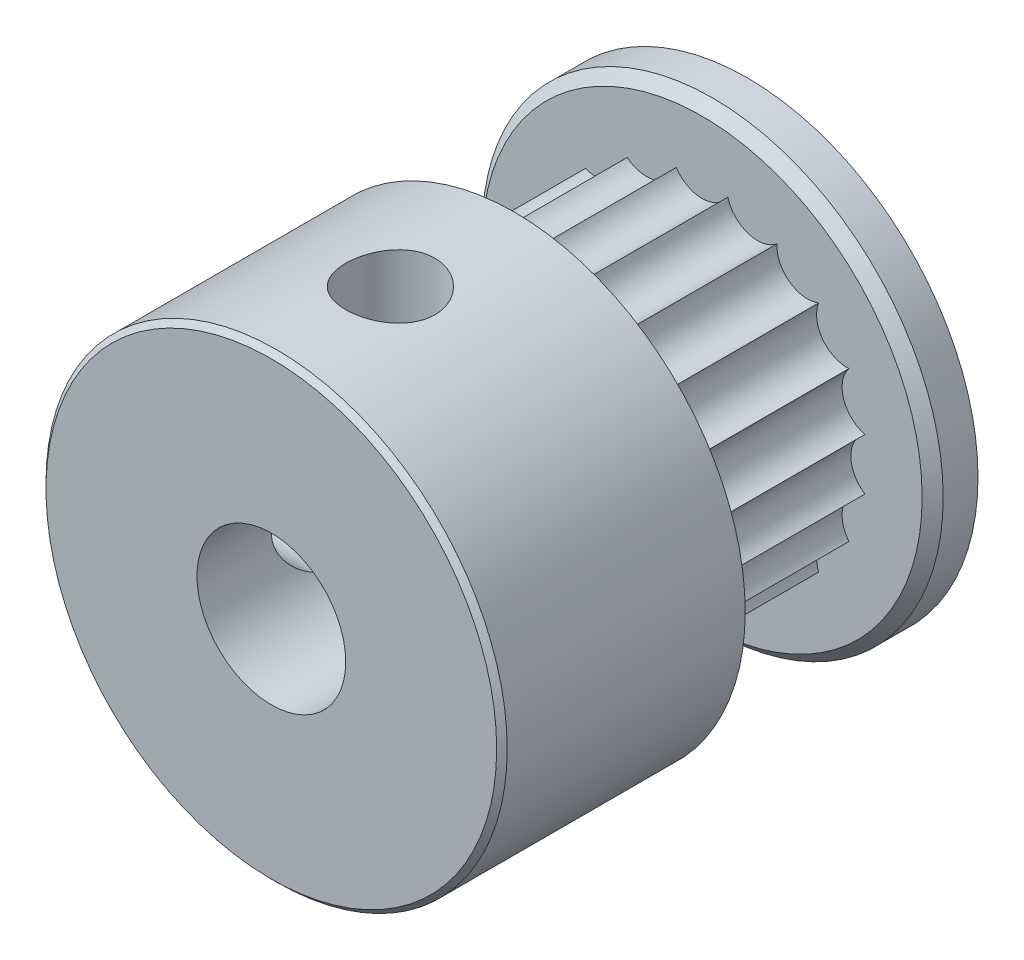
SolidWorks part; units mm, degrees
material "1060 Alloy"
ref_plane "Front Plane" through (0, 0, 0) normal (0, 0, 1) x (1, 0, 0)
ref_plane "Top Plane" through (0, 0, 0) normal (0, 1, 0) x (1, 0, 0)
ref_plane "Right Plane" through (0, 0, 0) normal (1, 0, 0) x (0, 0, -1)
sketch "Sketch1" plane through (0, 0, 0) normal (1, 0, 0) x (0, 0, -1)
  line L0 (-8, 0) -> (8, 0) construction
  line L1 (-7.8232, 7.75) -> (0.1768, 7.75)
  line L2 (0.1768, 7.75) -> (0.1768, 5)
  line L3 (0.1768, 5) -> (6.4768, 5)
  line L4 (6.4768, 5) -> (6.4768, 7.3964)
  line L5 (6.4768, 7.3964) -> (6.8303, 7.75)
  line L6 (6.8303, 7.75) -> (8, 7.75)
  line L7 (8, 7.75) -> (8, 2.5)
  line L8 (-7.8232, 7.75) -> (-8, 7.5732)
  line L9 (-8, 7.5732) -> (-8, 2.5)
  line L10 (8, 2.5) -> (-8, 2.5)
  point P4 (0, 0)
  dimension "D1" = 16
  dimension "D2" = 7.75
  dimension "D3" = 8
  dimension "D4" = 2.5
  dimension "D5" = 6.3
  dimension "D6" = 0.25
  dimension "D7" = 45
  dimension "D8" = 45
  dimension "D9" = 0.5
  dimension "D10" = 5
revolve "Revolve1" add sketch "Sketch1" angle 360 about L0
sketch "Sketch2" plane through (0, 0, 0) normal (0, 1, 0) x (1, 0, 0)
  line L0 (-7.5732, -8) -> (7.5732, -8) construction
  circle A0 centre (0, -4) radius 1.5
  dimension "D2" = 3
  dimension "D1" = 4
extrude "Cut-Extrude1" cut sketch "Sketch2" along normal blind 29
pattern_circular "CirPattern1" count 2 over 90 about axis through (0, 0, 8) along (0, 0, 1) of "Cut-Extrude1"
sketch "Sketch3" plane through (0, 0, -6.4768) normal (0, 0, 1) x (1, 0, 0)
  arc A0 (-0.8666, 5.4716) -> (0.8666, 5.4716) centre (0, 6.0321) ccw
  circle A1 centre (0, 0) radius 5 construction
  arc A2 (0.8666, 5.4716) -> (2.515, 4.936) centre (1.864, 5.7369) ccw
  arc A3 (2.515, 4.936) -> (3.9172, 3.9172) centre (3.5456, 4.8801) ccw
  arc A4 (3.9172, 3.9172) -> (4.936, 2.515) centre (4.8801, 3.5456) ccw
  arc A5 (4.936, 2.515) -> (5.4716, 0.8666) centre (5.7369, 1.864) ccw
  arc A6 (5.4716, 0.8666) -> (5.4716, -0.8666) centre (6.0321, 0) ccw
  arc A7 (5.4716, -0.8666) -> (4.936, -2.515) centre (5.7369, -1.864) ccw
  arc A8 (4.936, -2.515) -> (3.9172, -3.9172) centre (4.8801, -3.5456) ccw
  arc A9 (3.9172, -3.9172) -> (2.515, -4.936) centre (3.5456, -4.8801) ccw
  arc A10 (2.515, -4.936) -> (0.8666, -5.4716) centre (1.864, -5.7369) ccw
  arc A11 (0.8666, -5.4716) -> (-0.8666, -5.4716) centre (0, -6.0321) ccw
  arc A12 (-0.8666, -5.4716) -> (-2.515, -4.936) centre (-1.864, -5.7369) ccw
  arc A13 (-2.515, -4.936) -> (-3.9172, -3.9172) centre (-3.5456, -4.8801) ccw
  arc A14 (-3.9172, -3.9172) -> (-4.936, -2.515) centre (-4.8801, -3.5456) ccw
  arc A15 (-4.936, -2.515) -> (-5.4716, -0.8666) centre (-5.7369, -1.864) ccw
  arc A16 (-5.4716, -0.8666) -> (-5.4716, 0.8666) centre (-6.0321, 0) ccw
  arc A17 (-5.4716, 0.8666) -> (-4.936, 2.515) centre (-5.7369, 1.864) ccw
  arc A18 (-4.936, 2.515) -> (-3.9172, 3.9172) centre (-4.8801, 3.5456) ccw
  arc A19 (-3.9172, 3.9172) -> (-2.515, 4.936) centre (-3.5456, 4.8801) ccw
  arc A20 (-2.515, 4.936) -> (-0.8666, 5.4716) centre (-1.864, 5.7369) ccw
  circle A21 centre (0, 0) radius 5.5398 construction
  circle A22 centre (0, 0) radius 2.5 construction
  circle A23 centre (0, 0) radius 2.5
  dimension "D2" = 20
extrude "Boss-Extrude1" add sketch "Sketch3" along normal up to surface (6.3 mm away) up to face at (7.75, 0, -0.1768)
